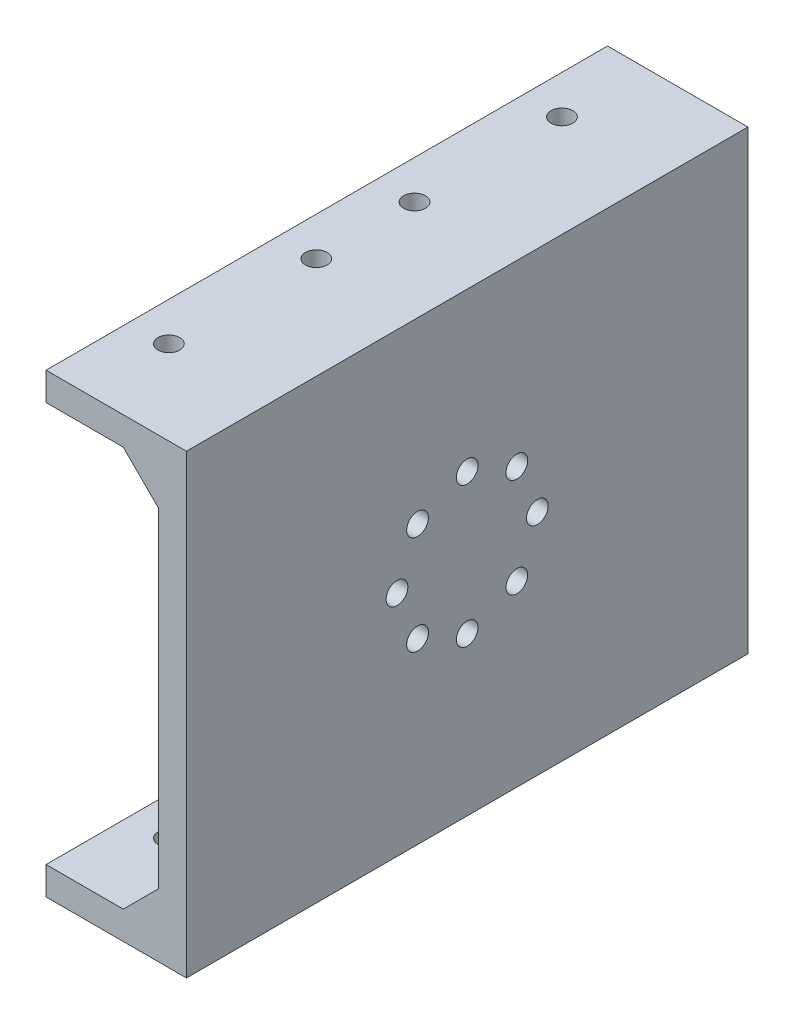
SolidWorks part; units mm, degrees
material "6061-T6 (SS)"
ref_plane "前视基准面" through (0, 0, 0) normal (0, 0, 1) x (1, 0, 0)
ref_plane "上视基准面" through (0, 0, 0) normal (0, 1, 0) x (1, 0, 0)
ref_plane "右视基准面" through (0, 0, 0) normal (1, 0, 0) x (0, 0, -1)
sketch "草图1" plane through (0, 0, 0) normal (0, 0, 1) x (1, 0, 0)
  line L0 (0, 0) -> (20, 0)
  line L1 (20, 0) -> (20, 65)
  line L2 (20, 65) -> (0, 65)
  dimension "D1" = 65
  dimension "D2" = 20
extrude "拉伸-薄壁1" add sketch "草图1" along normal blind 80 thin thin type one direction reverse wall 4
chamfer "倒角1" distance 5 angle 45 2 edges at (16, 4, 40) (16, 61, 40)
sketch "草图2" plane through (0, 61, 0) normal (0, -1, 0) x (1, 0, 0)
  line L0 (5.5, 0) -> (5.5, 80) construction
  line L1 (11, 0) -> (0, 0) construction
  line L2 (11, 80) -> (0, 80) construction
  line L3 (11, 40) -> (0, 40) construction
  line L4 (11, 0) -> (11, 80) construction
  line L5 (0, 80) -> (0, 0) construction
  circle A0 centre (5.5, 12) radius 1.55
  circle A1 centre (5.5, 68) radius 1.55
  circle A2 centre (5.5, 33) radius 1.55
  circle A3 centre (5.5, 47) radius 1.55
  dimension "D1" = 3.1
  dimension "D2" = 12
  dimension "D3" = 35
extrude "切除-拉伸1" cut sketch "草图2" against normal mid plane 500
sketch "草图3" plane through (20, 0, 0) normal (1, 0, 0) x (0, 0, -1)
  line L0 (-80, 32.5) -> (0, 32.5) construction
  line L1 (-80, 0) -> (-80, 65) construction
  line L2 (0, 0) -> (0, 65) construction
  line L3 (-40, 65) -> (-40, 0) construction
  line L4 (-80, 65) -> (0, 65) construction
  line L5 (-80, 0) -> (0, 0) construction
  circle A0 centre (-40, 32.5) radius 10 construction
  circle A1 centre (-40, 42.5) radius 1.55
  circle A2 centre (-32.9289, 39.5711) radius 1.55
  circle A3 centre (-30, 32.5) radius 1.55
  circle A4 centre (-32.9289, 25.4289) radius 1.55
  circle A5 centre (-40, 22.5) radius 1.55
  circle A6 centre (-47.0711, 25.4289) radius 1.55
  circle A7 centre (-50, 32.5) radius 1.55
  circle A8 centre (-47.0711, 39.5711) radius 1.55
  point P33 (-40, 32.5)
  dimension "D1" = 20
  dimension "D2" = 3.1
  dimension "D3" = 8
extrude "切除-拉伸2" cut sketch "草图3" against normal through all
